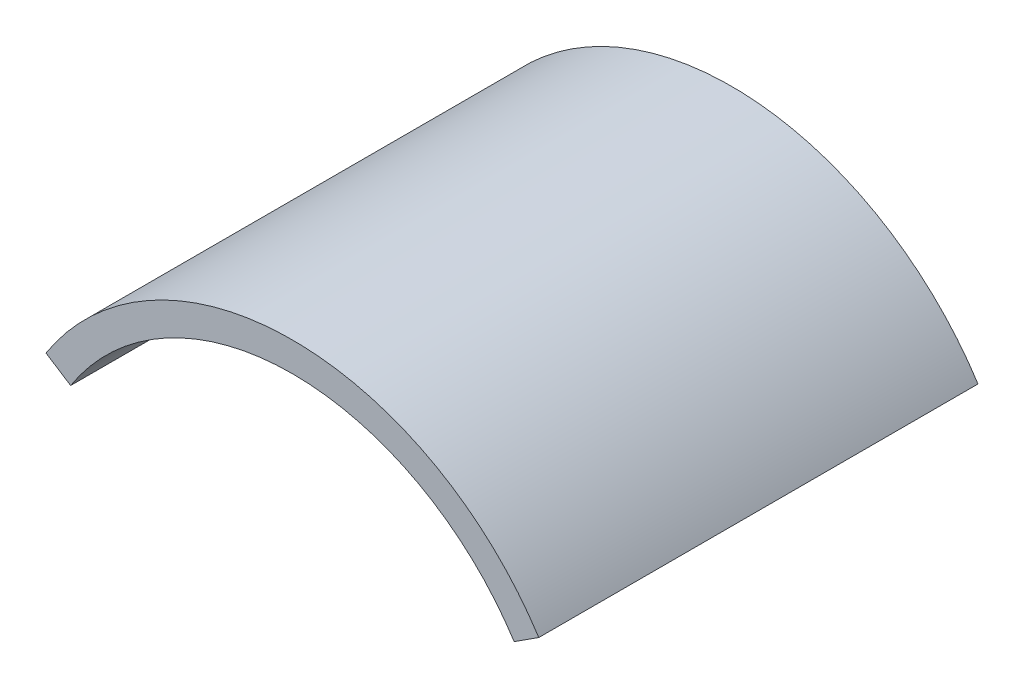
SolidWorks part; units mm, degrees
material "Acrylic (Medium-high impact)"
ref_plane "Front Plane" through (0, 0, 0) normal (0, 0, 1) x (1, 0, 0)
ref_plane "Top Plane" through (0, 0, 0) normal (0, 1, 0) x (1, 0, 0)
ref_plane "Right Plane" through (0, 0, 0) normal (1, 0, 0) x (0, 0, -1)
sketch "Sketch4" plane through (0, 0, 0) normal (0, 0, 1) x (1, 0, 0)
  line L0 (-16.8293, 10.8063) -> (-15.1463, 9.7256)
  line L1 (15.1463, 9.7256) -> (16.8293, 10.8063)
  arc A0 (15.1463, 9.7256) -> (-15.1463, 9.7256) centre (0, 0) ccw
  arc A1 (16.8293, 10.8063) -> (-16.8293, 10.8063) centre (0, 0) ccw
  dimension "D1" = 2
sketch "Sketch5" plane through (0, 0, 0) normal (0, 1, 0) x (1, 0, 0)
  line L0 (0, 0) -> (0, 30)
sweep "Sensor Cover" add profiles "Sketch4" path "Sketch5"
